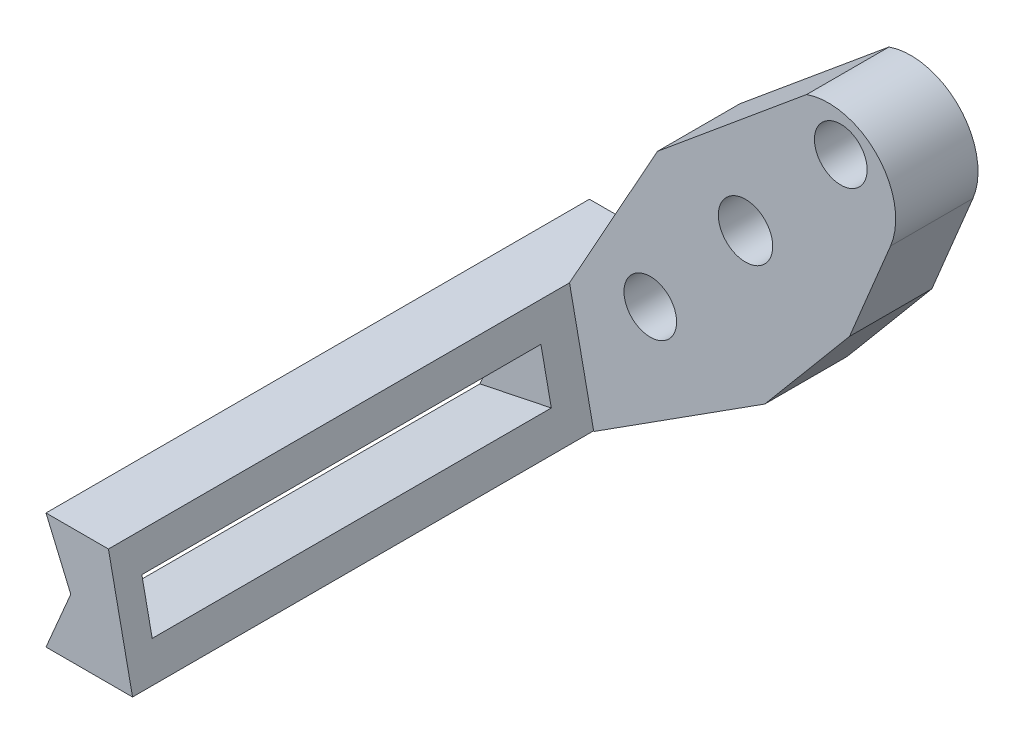
SolidWorks part; units mm, degrees
ref_plane "Alzado" through (0, 0, 0) normal (0, 0, 1) x (1, 0, 0)
ref_plane "Planta" through (0, 0, 0) normal (0, 1, 0) x (1, 0, 0)
ref_plane "Vista lateral" through (0, 0, 0) normal (1, 0, 0) x (0, 0, -1)
sketch "Croquis1" plane through (0, 0, 0) normal (0, 0, 1) x (1, 0, 0)
  line L6 (-19.8137, 27.4082) -> (-22.3447, 27.4082)
  line L7 (-20.8419, 23.8815) -> (-22.3447, 20.3547)
  line L8 (-22.3447, 27.4082) -> (-20.8419, 23.8815)
  line L9 (-22.3447, 20.3547) -> (-19.8137, 20.3547)
  line L13 (-6.6939, 26.9607) -> (-1.5516, 33.0891)
  line L14 (-1.5516, 33.0891) -> (0.9412, 39.0897)
  line L17 (-13.2134, 36.9925) -> (-18.5532, 27.4082)
  line L18 (-17.0573, 20.3378) -> (-6.6939, 26.9607)
  line L21 (-13.2134, 36.9925) -> (-4.1535, 44.5102)
  line L22 (-19.8137, 27.4082) -> (-18.5532, 27.4082)
  line L23 (-19.8137, 20.3547) -> (-17.0892, 20.3547)
  arc A2 (-17.0892, 20.3547) -> (-17.0573, 20.3378) centre (-15.1976, 23.8815) ccw
  circle A3 centre (-2.0816, 42.3866) radius 1.601
  circle A4 centre (-7.8659, 35.4914) radius 1.6509
  circle A5 centre (-13.6492, 28.5982) radius 1.5982
  arc A6 (0.9412, 39.0897) -> (-4.1535, 44.5102) centre (-2.825, 40.6543) ccw
extrude "Saliente-Extruir1" add sketch "Croquis1" along normal blind 5
sketch "Croquis2" plane through (0, 0, 5) normal (0, 0, 1) x (1, 0, 0)
  line L0 (-22.3447, 20.3547) -> (-17.0892, 20.3547) construction
  line L1 (-20.8419, 23.8815) -> (-22.3447, 20.3547) construction
  line L2 (-18.5532, 27.4082) -> (-22.3447, 27.4082) construction
  line L3 (-22.3447, 27.4082) -> (-20.8419, 23.8815) construction
  line L4 (-22.3447, 20.3547) -> (-17.0892, 20.3547)
  line L5 (-20.8419, 23.8815) -> (-22.3447, 20.3547)
  line L6 (-18.5532, 27.4082) -> (-22.3447, 27.4082)
  line L7 (-22.3447, 27.4082) -> (-20.8419, 23.8815)
  line L9 (-18.5532, 27.4082) -> (-17.0892, 20.3547)
extrude "Saliente-Extruir2" add sketch "Croquis2" along normal blind 28
sketch "Croquis3" plane through (-12.3331, -2.5598, 0) normal (0.9791, 0.2032, 0) x (0, 0, -1)
  line L0 (-33, 30.6068) -> (-5, 30.6068) construction
  line L1 (-7.1436, 28.6068) -> (-31.3783, 28.6068)
  line L2 (-7.1436, 28.6068) -> (-7.1436, 25.5068)
  line L3 (-7.1436, 25.5068) -> (-31.3783, 25.5068)
  line L4 (-31.3783, 28.6068) -> (-31.3783, 25.5068)
  dimension "D1" = 3.1
  dimension "D2" = 2
extrude "Cortar-Extruir2" cut sketch "Croquis3" against normal blind 35
